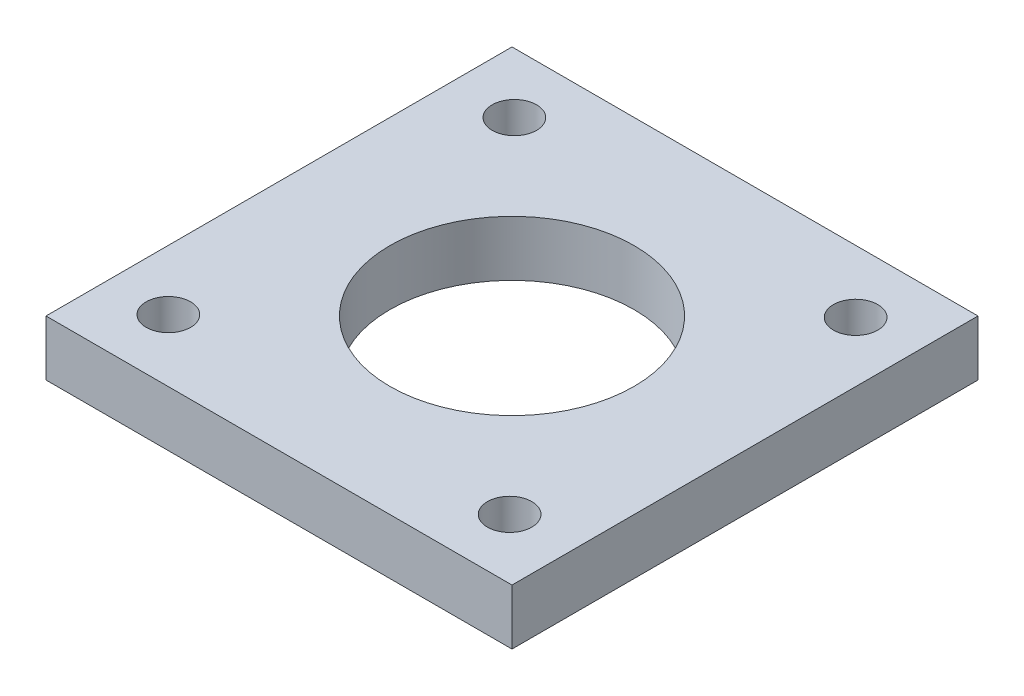
SolidWorks part; units mm, degrees
ref_plane "Front Plane" through (0, 0, 0) normal (0, 0, 1) x (1, 0, 0)
ref_plane "Top Plane" through (0, 0, 0) normal (0, 1, 0) x (1, 0, 0)
ref_plane "Right Plane" through (0, 0, 0) normal (1, 0, 0) x (0, 0, -1)
sketch "Sketch1" plane through (0, 0, 0) normal (0, 1, 0) x (1, 0, 0)
  line L0 (0, 0) -> (-19.9263, 20.2042) construction
  line L1 (0, 0) -> (17.8956, 17.6494) construction
  line L2 (0, 0) -> (17.1358, -17.3748) construction
  line L3 (0, 0) -> (-18.3532, -18.1007) construction
  line L5 (-21, -21) -> (21, -21)
  line L6 (-21, -21) -> (-21, 21)
  line L7 (-21, 21) -> (21, 21)
  line L8 (21, -21) -> (21, 21)
  line L9 (-21, -21) -> (21, 21) construction
  line L10 (-21, 21) -> (21, -21) construction
  circle A0 centre (0, 0) radius 11
  circle A1 centre (-15.5925, -15.378) radius 2
  circle A2 centre (-15.378, 15.5925) radius 2
  circle A3 centre (15.5925, 15.378) radius 2
  circle A4 centre (15.378, -15.5925) radius 2
  dimension "D1" = 22
  dimension "D2" = 4
  dimension "D4" = 21.9
  dimension "D3" = 21.9
  dimension "D5" = 21.9
  dimension "D6" = 21.9
  dimension "D7" = 42
extrude "Boss-Extrude1" add sketch "Sketch1" along normal blind 5
